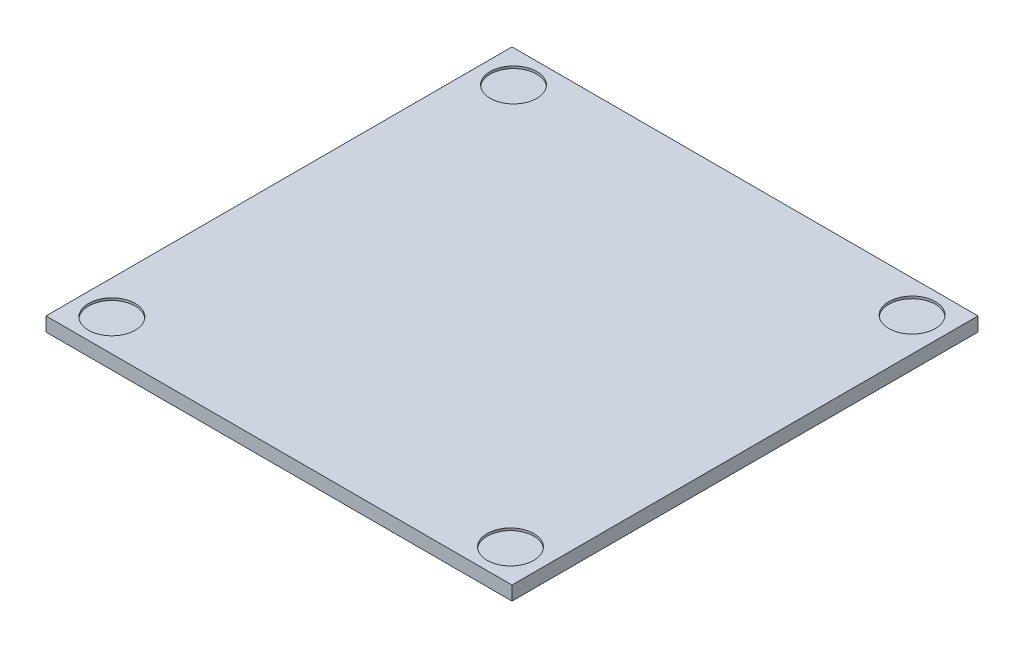
SolidWorks part; units mm, degrees
ref_plane "Front Plane" through (0, 0, 0) normal (0, 0, 1) x (1, 0, 0)
ref_plane "Top Plane" through (0, 0, 0) normal (0, 1, 0) x (1, 0, 0)
ref_plane "Right Plane" through (0, 0, 0) normal (1, 0, 0) x (0, 0, -1)
sketch "Sketch1" plane through (0, 0, 0) normal (0, 1, 0) x (1, 0, 0)
  line L1 (0, 0) -> (1000, 0)
  line L2 (0, 0) -> (0, -1000)
  line L3 (0, -1000) -> (1000, -1000)
  line L4 (1000, 0) -> (1000, -1000)
  dimension "D1" = 1000
  dimension "D2" = 1000
extrude "Boss-Extrude1" add sketch "Sketch1" along normal blind 30
sketch "Sketch2" plane through (0, 30, 0) normal (0, 1, 0) x (1, 0, 0)
  line L0 (500, 38.0939) -> (500, -1087.6199) construction
  line L1 (0, 0) -> (0, -1000) construction
  line L2 (-119.7449, -500) -> (1170.6095, -500) construction
  line L3 (0, -1000) -> (1000, -1000) construction
  circle A0 centre (72.3156, -69.0685) radius 50
  circle A1 centre (927.6844, -69.0685) radius 50
  circle A2 centre (927.6844, -930.9315) radius 50
  circle A3 centre (72.3156, -930.9315) radius 50
  dimension "D1" = 100
  dimension "D2" = 500
  dimension "D3" = 500
extrude "Cut-Extrude1" cut sketch "Sketch2" against normal blind 5
